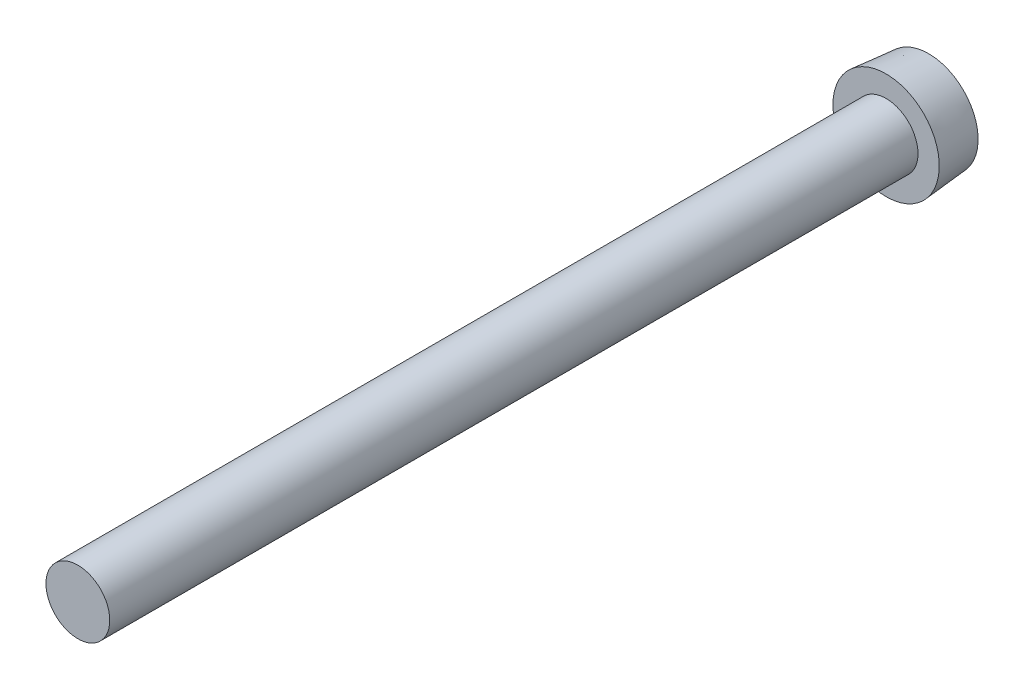
SolidWorks part; units mm, degrees
ref_plane "Plan de face" through (0, 0, 0) normal (0, 0, 1) x (1, 0, 0)
ref_plane "Plan de dessus" through (0, 0, 0) normal (0, 1, 0) x (1, 0, 0)
ref_plane "Plan de droite" through (0, 0, 0) normal (1, 0, 0) x (0, 0, -1)
sketch "Esquisse1" plane through (0, 0, 0) normal (0, 0, 1) x (1, 0, 0)
  circle A0 centre (0, 0) radius 1.5
  dimension "D1" = 3
extrude "Boss.-Extru.1" add sketch "Esquisse1" along normal blind 38
sketch "Esquisse2" plane through (0, 0, 0) normal (0, 0, -1) x (-1, 0, 0)
  circle A0 centre (0, 0) radius 2.5
  circle A1 centre (0, 0) radius 1.5 construction
  circle A2 centre (0, 0) radius 1.5 construction
  dimension "D1" = 1
extrude "Boss.-Extru.2" add sketch "Esquisse2" along normal blind 2 draft 5
